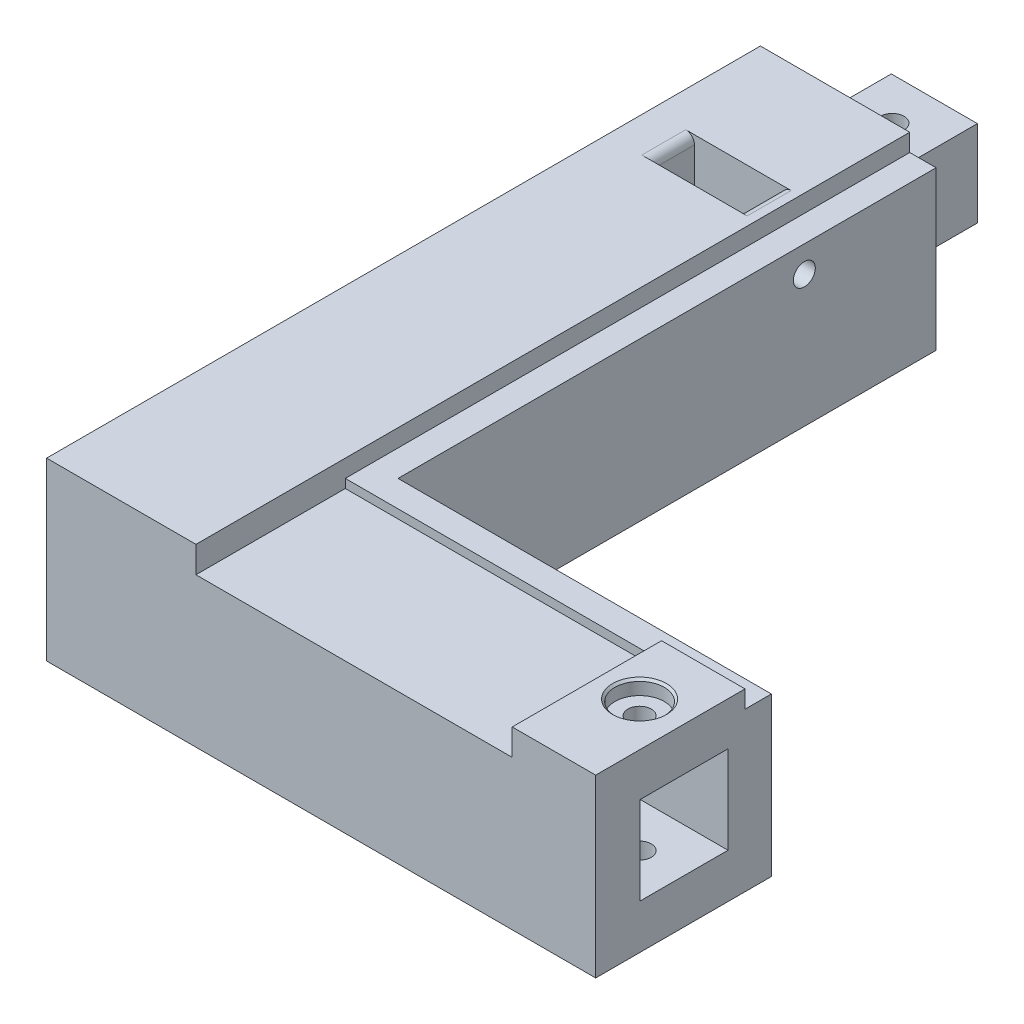
SolidWorks part; units mm, degrees
ref_plane "Front Plane" through (0, 0, 0) normal (0, 0, 1) x (1, 0, 0)
ref_plane "Top Plane" through (0, 0, 0) normal (0, 1, 0) x (1, 0, 0)
ref_plane "Right Plane" through (0, 0, 0) normal (1, 0, 0) x (0, 0, -1)
sketch "Sketch2" plane through (0, 0, 0) normal (0, 1, 0) x (1, 0, 0)
  line L0 (-50.8, 155.575) -> (0, 155.575)
  line L1 (0, 0) -> (107.95, 0)
  line L2 (0, 0) -> (0, 155.575)
  line L5 (-50.8, -50.8) -> (107.95, -50.8)
  line L6 (-50.8, -50.8) -> (-50.8, 155.575)
  line L11 (107.95, 0) -> (107.95, -50.8)
  point P5 (-50.8, -50.8)
  dimension "D1" = 206.375
  dimension "D2" = 50.8
  dimension "D3" = 50.8
  dimension "D4" = 158.75
extrude "Boss-Extrude1" add sketch "Sketch2" along normal blind 50.8
sketch "Sketch3" plane through (107.95, 0, 0) normal (1, 0, 0) x (0, 0, -1)
  line L1 (-37.9399, 12.8601) -> (-12.5399, 12.8601)
  line L2 (-37.9399, 12.8601) -> (-37.9399, 38.2601)
  line L3 (-37.9399, 38.2601) -> (-12.5399, 38.2601)
  line L4 (-12.5399, 12.8601) -> (-12.5399, 38.2601)
  line L5 (-37.9399, 12.8601) -> (-12.5399, 38.2601) construction
  line L6 (-37.9399, 38.2601) -> (-12.5399, 12.8601) construction
  point P0 (-25.2399, 25.5601)
  dimension "D1" = 25.4
extrude "Cut-Extrude1" cut sketch "Sketch3" against normal blind 25.4
sketch "Sketch6" plane through (0, 50.8, 0) normal (0, 1, 0) x (1, 0, 0)
  line L0 (107.95, 0) -> (0, 0) construction
  line L1 (107.95, -50.8) -> (107.95, 0) construction
  point P0 (95.25, -25.4)
  dimension "D1" = 25.4
  dimension "D2" = 12.7
hole_wizard "CBORE for 1/4 Binding Head Machine Screw1" positions "Sketch6" profile "Sketch7" counterbore size "1/4" standard "ANSI Inch" end condition through all
sketch "Sketch7" plane through (95.25, 50.8, 25.4) normal (1, 0, 0) x (0, 0, 1)
  line L0 (0, 0) -> (0, 50.8)
  line L1 (0, 50.8) -> (3.3782, 50.8)
  line L3 (3.3782, 50.8) -> (3.3782, 4.191)
  line L4 (7.1437, 4.191) -> (3.3782, 4.191)
  line L5 (7.1437, 4.191) -> (7.1437, 0.635)
  line L6 (7.1437, 0.635) -> (7.7788, 0)
  line L7 (7.7788, 0) -> (0, 0)
  line L8 (-7.1437, 0.635) -> (-7.7788, 0) construction
  line L11 (0, -6.35) -> (0, 107.95) construction
  dimension "Thru Hole Dia." = 6.7564
  dimension "Thru Hole Depth" = 50.8
  dimension "C'Bore Dia." = 14.2875
  dimension "C'Bore Depth" = 4.191
  dimension "Near C'Sink Dia." = 15.5575
  dimension "Near C'Sink Angle" = 90
sketch "Sketch8" plane through (0, 0, -155.575) normal (0, 0, -1) x (-1, 0, 0)
  line L0 (0, 50.8) -> (0, 0) construction
  line L1 (12.954, 12.954) -> (37.846, 12.954)
  line L2 (12.954, 12.954) -> (12.954, 37.846)
  line L3 (12.954, 37.846) -> (37.846, 37.846)
  line L4 (37.846, 12.954) -> (37.846, 37.846)
  line L5 (12.954, 12.954) -> (37.846, 37.846) construction
  line L6 (12.954, 37.846) -> (37.846, 12.954) construction
  line L8 (0, 50.8) -> (50.8, 50.8) construction
  point P0 (25.4, 25.4)
  dimension "D1" = 24.892
  dimension "D2" = 25.4
  dimension "D3" = 25.4
extrude "Boss-Extrude2" add sketch "Sketch8" along normal blind 24.892
sketch "Sketch12" plane through (0, 37.846, 0) normal (0, 1, 0) x (1, 0, 0)
  line L1 (-37.846, 180.467) -> (-37.846, 155.575) construction
  line L2 (0, 155.575) -> (-50.8, 155.575) construction
  circle A0 centre (-25.4, 168.275) radius 3.429
  dimension "D1" = 6.858
  dimension "D2" = 12.7
  dimension "D3" = 12.446
extrude "Cut-Extrude2" cut sketch "Sketch12" against normal blind 25.4
sketch "Sketch13" plane through (0, 50.8, 0) normal (0, 1, 0) x (1, 0, 0)
  line L0 (-50.8, 155.575) -> (-50.8, -50.8) construction
  line L1 (-38.1, 111.125) -> (-12.7, 111.125)
  line L2 (-38.1, 111.125) -> (-38.1, 123.825)
  line L3 (-38.1, 123.825) -> (-12.7, 123.825)
  line L4 (-12.7, 111.125) -> (-12.7, 123.825)
  line L5 (-38.1, 111.125) -> (-12.7, 123.825) construction
  line L6 (-38.1, 123.825) -> (-12.7, 111.125) construction
  line L7 (63.5, -12.7) -> (76.2, -12.7)
  line L8 (63.5, -12.7) -> (63.5, -38.1)
  line L9 (63.5, -38.1) -> (76.2, -38.1)
  line L10 (76.2, -12.7) -> (76.2, -38.1)
  line L11 (63.5, -12.7) -> (76.2, -38.1) construction
  line L12 (63.5, -38.1) -> (76.2, -12.7) construction
  line L14 (107.95, 0) -> (0, 0) construction
  line L16 (0, 155.575) -> (-50.8, 155.575) construction
  line L17 (107.95, -50.8) -> (107.95, 0) construction
  point P0 (-25.4, 117.475)
  point P5 (69.85, -25.4)
  dimension "D1" = 25.4
  dimension "D2" = 12.7
  dimension "D3" = 12.7
  dimension "D4" = 38.1
  dimension "D5" = 25.4
  dimension "D6" = 12.7
  dimension "D7" = 12.7
  dimension "D8" = 38.1
extrude "Cut-Extrude3" cut sketch "Sketch13" against normal blind 25.908 contours L3 L4 L1 L2
fillet "Fillet1" radius 2.54 2 edges at (-12.7, 50.8, -117.475) (-38.1, 50.8, -117.475)
sketch "Sketch14" plane through (-50.8, 0, 0) normal (-1, 0, 0) x (0, 0, 1)
  line L0 (-155.575, 50.8) -> (-155.575, 0) construction
  line L1 (-155.575, 50.8) -> (50.8, 50.8) construction
  circle A0 centre (-117.475, 38.1) radius 3.175
  dimension "D1" = 6.35
  dimension "D2" = 38.1
  dimension "D3" = 12.7
sketch "Sketch15" plane through (0, 0, 50.8) normal (0, 0, 1) x (1, 0, 0)
  line L0 (-50.8, 50.8) -> (107.95, 50.8) construction
  line L1 (107.95, 50.8) -> (107.95, 0) construction
  circle A0 centre (69.85, 38.1) radius 3.175
  dimension "D1" = 6.35
  dimension "D2" = 12.7
  dimension "D3" = 38.1
extrude "Cut-Extrude5" cut sketch "Sketch14" against normal through all
sketch "Sketch17" plane through (0, 50.8, 0) normal (0, 1, 0) x (1, 0, 0)
  line L0 (0, 155.575) -> (0, 0)
  line L1 (0, 0) -> (107.95, 0)
  line L2 (107.95, 0) -> (107.95, -7.62)
  line L3 (107.95, -50.8) -> (107.95, 0) construction
  line L4 (107.95, -7.62) -> (-7.62, -7.62)
  line L5 (-7.62, -7.62) -> (-7.62, 155.575)
  line L6 (0, 155.575) -> (-50.8, 155.575) construction
  line L7 (-7.62, 155.575) -> (0, 155.575)
  dimension "D1" = 7.62
  dimension "D2" = 7.62
extrude "Cut-Extrude6" cut sketch "Sketch17" against normal blind 5.08
sketch "Sketch18" plane through (0, 50.8, 0) normal (0, 1, 0) x (1, 0, 0)
  line L0 (-50.8, -50.8) -> (107.95, -50.8) construction
  line L1 (-7.62, -7.62) -> (83.82, -7.62)
  line L2 (-7.62, -7.62) -> (-7.62, -50.8)
  line L3 (-7.62, -50.8) -> (83.82, -50.8)
  line L4 (83.82, -7.62) -> (83.82, -50.8)
  dimension "D1" = 91.44
extrude "Cut-Extrude7" cut sketch "Sketch18" against normal blind 7.62
